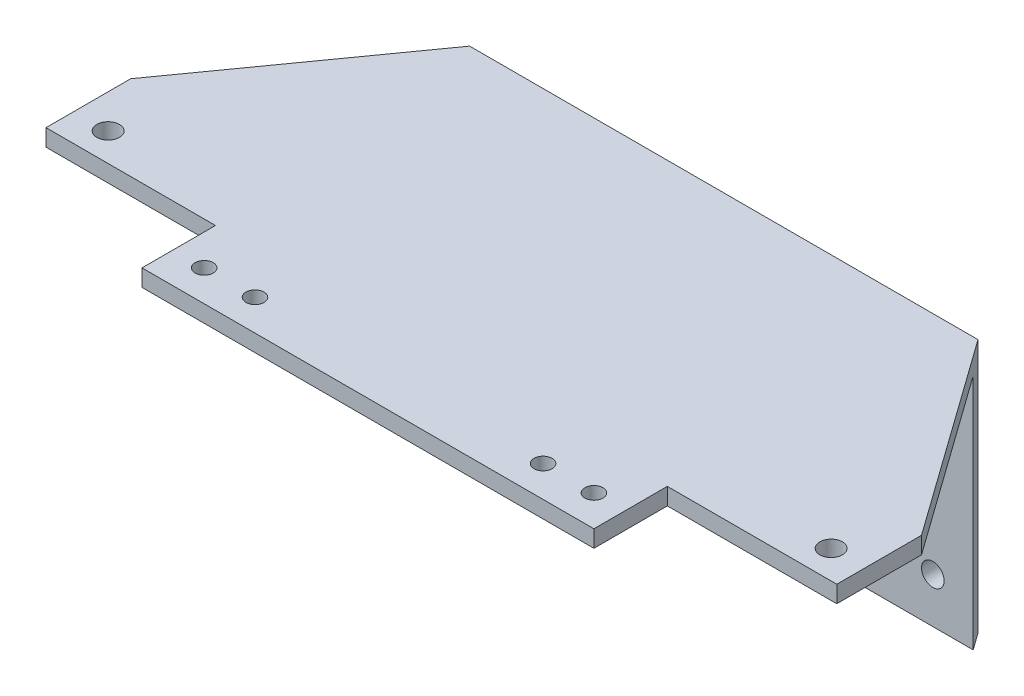
SolidWorks part; units mm, degrees
ref_plane "前视基准面" through (0, 0, 0) normal (0, 0, 1) x (1, 0, 0)
ref_plane "上视基准面" through (0, 0, 0) normal (0, 1, 0) x (1, 0, 0)
ref_plane "右视基准面" through (0, 0, 0) normal (1, 0, 0) x (0, 0, -1)
sketch "草图1" plane through (0, 0, 0) normal (1, 0, 0) x (0, 0, -1)
  line L0 (22, 19.5) -> (22, -22.5)
  line L1 (-25, 22.5) -> (25, 22.5) construction
  line L2 (-25, 22.5) -> (-25, -22.5) construction
  line L3 (-25, -22.5) -> (25, -22.5) construction
  line L4 (25, 22.5) -> (25, -22.5) construction
  line L5 (-25, 22.5) -> (25, -22.5) construction
  line L6 (-25, -22.5) -> (25, 22.5) construction
  line L7 (-25, 22.5) -> (25, 22.5) construction
  line L8 (-25, 22.5) -> (-25, 19.5) construction
  line L9 (-25, 19.5) -> (25, 19.5) construction
  line L10 (25, 22.5) -> (25, 19.5) construction
  line L11 (-25, 22.5) -> (25, 19.5) construction
  line L12 (-25, 19.5) -> (25, 22.5) construction
  line L13 (25, 22.5) -> (22, 22.5) construction
  line L14 (25, 22.5) -> (25, -22.5) construction
  line L15 (25, -22.5) -> (22, -22.5) construction
  line L16 (22, 22.5) -> (22, -22.5) construction
  line L17 (25, 22.5) -> (22, -22.5) construction
  line L18 (25, -22.5) -> (22, 22.5) construction
  line L19 (22, -22.5) -> (25, -22.5)
  line L20 (25, -22.5) -> (25, 22.5)
  line L21 (25, 22.5) -> (-25, 22.5)
  line L22 (-25, 22.5) -> (-25, 19.5)
  line L23 (-25, 19.5) -> (22, 19.5)
  point P0 (0, 0)
  point P8 (0, 21)
  point P11 (23.5, 0)
  point P12 (22, 19.5)
  dimension "D1" = 45
  dimension "D2" = 50
  dimension "D3" = 3
  dimension "D4" = 3
extrude "凸台-拉伸1" add sketch "草图1" along normal blind 140
sketch "草图2" plane through (0, 0, -25) normal (0, 0, -1) x (-1, 0, 0)
  line L0 (-140, 22.5) -> (0, 22.5) construction
  line L1 (-140, 22.5) -> (0, 22.5) construction
  line L2 (-140, 22.5) -> (-140, -22.5) construction
  line L3 (-140, -22.5) -> (0, -22.5) construction
  line L4 (0, 22.5) -> (0, -22.5) construction
  line L5 (-140, 22.5) -> (0, -22.5) construction
  line L6 (-140, -22.5) -> (0, 22.5) construction
  line L7 (-140, -22.5) -> (-140, 22.5) construction
  line L9 (-110, 22.5) -> (-30, 22.5) construction
  line L10 (-110, 22.5) -> (-110, -22.5) construction
  line L11 (-110, -22.5) -> (-30, -22.5) construction
  line L12 (-30, 22.5) -> (-30, -22.5) construction
  line L13 (-110, 22.5) -> (-30, -22.5) construction
  line L14 (-110, -22.5) -> (-30, 22.5) construction
  line L15 (-110, 22.5) -> (-30, 22.5) construction
  line L16 (-110, 22.5) -> (-110, -14.5) construction
  line L17 (-110, -14.5) -> (-30, -14.5) construction
  line L18 (-30, 22.5) -> (-30, -14.5) construction
  line L19 (-110, 22.5) -> (-30, -14.5) construction
  line L20 (-110, -14.5) -> (-30, 22.5) construction
  circle A0 centre (-110, -14.5) radius 2
  circle A1 centre (-30, -14.5) radius 2
  point P4 (-70, 0)
  point P10 (-70, 0)
  point P17 (-70, 4)
  dimension "D2" = 37
  dimension "D1" = 80
extrude "切除-拉伸1" cut sketch "草图2" against normal up to next
sketch "草图3" plane through (0, 22.5, 0) normal (0, 1, 0) x (1, 0, 0)
  line L1 (0, 25) -> (140, 25) construction
  line L2 (0, 25) -> (0, -25) construction
  line L3 (0, -25) -> (140, -25) construction
  line L4 (140, 25) -> (140, -25) construction
  line L5 (0, 25) -> (140, -25) construction
  line L6 (0, -25) -> (140, 25) construction
  line L7 (6, 25) -> (134, 25) construction
  line L8 (6, 25) -> (6, -25) construction
  line L9 (6, -25) -> (134, -25) construction
  line L10 (134, 25) -> (134, -25) construction
  line L11 (6, 25) -> (134, -25) construction
  line L12 (6, -25) -> (134, 25) construction
  line L13 (6, 25) -> (134, 25) construction
  line L14 (6, 25) -> (6, -20) construction
  line L15 (6, -20) -> (134, -20) construction
  line L16 (134, 25) -> (134, -20) construction
  line L17 (6, 25) -> (134, -20) construction
  line L18 (6, -20) -> (134, 25) construction
  circle A0 centre (6, -20) radius 2
  circle A1 centre (134, -20) radius 2
  point P4 (70, 0)
  point P7 (70, 0)
  point P14 (70, 2.5)
  dimension "D2" = 45
  dimension "D1" = 128
extrude "切除-拉伸2" cut sketch "草图3" against normal up to next
sketch "草图4" plane through (0, 22.5, 0) normal (0, 1, 0) x (1, 0, 0)
  line L0 (140, 25) -> (115, 25)
  line L1 (0, 25) -> (25, 25) construction
  line L2 (0, 25) -> (0, -10) construction
  line L3 (0, -10) -> (25, -10) construction
  line L4 (25, 25) -> (25, -10) construction
  line L5 (0, 25) -> (25, -10) construction
  line L6 (0, -10) -> (25, 25) construction
  line L7 (140, 25) -> (115, 25) construction
  line L8 (140, 25) -> (140, -10) construction
  line L9 (140, -10) -> (115, -10) construction
  line L10 (115, 25) -> (115, -10) construction
  line L11 (140, 25) -> (115, -10) construction
  line L12 (140, -10) -> (115, 25) construction
  line L13 (115, 25) -> (140, -10)
  line L14 (140, -10) -> (140, 25)
  line L15 (25, 25) -> (0, 25)
  line L16 (0, 25) -> (0, -10)
  line L17 (0, -10) -> (25, 25)
  point P4 (12.5, 7.5)
  point P10 (127.5, 7.5)
  dimension "D1" = 25
  dimension "D2" = 35
  dimension "D3" = 25
  dimension "D4" = 35
extrude "切除-拉伸3" cut sketch "草图4" against normal through all
ref_plane "基准面1" through (70, 0, 0) normal (-1, 0, 0) x (0, 0, 1)
sketch "草图9" plane through (70, 0, 0) normal (-1, 0, 0) x (0, 0, 1)
  line L0 (10, 19.5) -> (-22, 19.5) construction
  line L1 (-22, 19.5) -> (8.2328, 19.5) construction
  line L2 (-22, 19.5) -> (-22, -4.8939) construction
  line L3 (-22, -4.8939) -> (8.2328, -4.8939) construction
  line L4 (8.2328, 19.5) -> (8.2328, -4.8939) construction
  line L5 (-22, 19.5) -> (8.2328, -4.8939) construction
  line L6 (-22, -4.8939) -> (8.2328, 19.5) construction
  line L7 (-22, -4.8939) -> (8.2328, 19.5)
  point P5 (-6.8836, 7.303)
rib "筋2" sketch "草图9" sketch "草图9" thickness 10 extrusion direction parallel to sketch draft on no parameters "D1"=10
sketch "草图10" plane through (0, 0, 25) normal (0, 0, 1) x (1, 0, 0)
  line L1 (0, 22.5) -> (140, 22.5) construction
  line L2 (0, 22.5) -> (0, 19.5) construction
  line L3 (0, 19.5) -> (140, 19.5) construction
  line L4 (140, 22.5) -> (140, 19.5) construction
  line L5 (70, 19.5) -> (70, 22.5) construction
  line L6 (0, 21) -> (140, 21) construction
  line L7 (30, 22.5) -> (110, 22.5)
  line L8 (30, 22.5) -> (30, 19.5)
  line L9 (30, 19.5) -> (110, 19.5)
  line L10 (110, 22.5) -> (110, 19.5)
  line L11 (70, 19.5) -> (70, 22.5) construction
  line L12 (30, 21) -> (110, 21) construction
  point P4 (70, 21)
  point P284 (70, 21)
  dimension "D1" = 80
extrude "凸台-拉伸2" add sketch "草图10" along normal blind 13
sketch "草图11" plane through (0, 22.5, 0) normal (0, 1, 0) x (1, 0, 0)
  line L0 (35.5, -32.5) -> (44.5, -32.5) construction
  line L1 (30, -38) -> (110, -38) construction
  line L2 (30, -38) -> (30, -25) construction
  line L3 (30, -25) -> (110, -25) construction
  line L4 (110, -38) -> (110, -25) construction
  line L5 (70, -25) -> (70, -38) construction
  line L6 (30, -31.5) -> (110, -31.5) construction
  line L7 (30, -38) -> (50, -38) construction
  line L8 (30, -38) -> (30, -32.5) construction
  line L9 (30, -32.5) -> (50, -32.5) construction
  line L10 (50, -38) -> (50, -32.5) construction
  line L11 (40, -32.5) -> (40, -38) construction
  line L12 (30, -35.25) -> (50, -35.25) construction
  circle A0 centre (35.5, -32.5) radius 1.6
  circle A1 centre (44.5, -32.5) radius 1.6
  circle A2 centre (95.5, -32.5) radius 1.6
  circle A3 centre (104.5, -32.5) radius 1.6
  point P10 (40, -32.5)
  point P163 (40, -35.25)
  point P372 (70, -31.5)
  dimension "D1" = 5.5
  dimension "D2" = 20
  dimension "D3" = 9
extrude "切除-拉伸4" cut sketch "草图11" against normal up to surface (3 mm away) up to face at (6, 19.5, 22)
